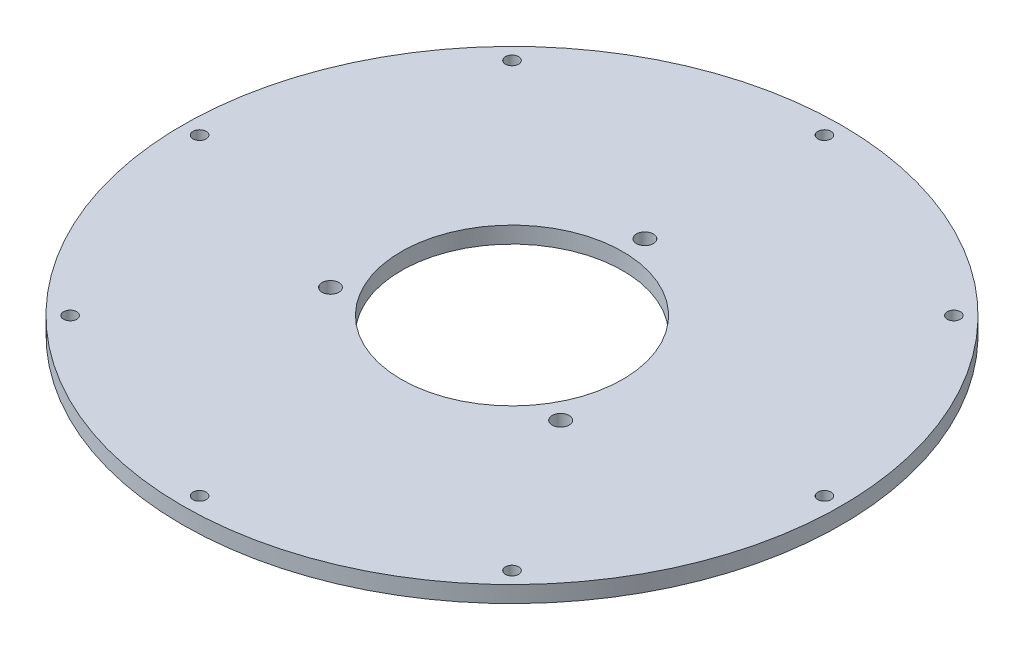
SolidWorks part; units mm, degrees
ref_plane "Front Plane" through (0, 0, 0) normal (0, 0, 1) x (1, 0, 0)
ref_plane "Top Plane" through (0, 0, 0) normal (0, 1, 0) x (1, 0, 0)
ref_plane "Right Plane" through (0, 0, 0) normal (1, 0, 0) x (0, 0, -1)
sketch "Sketch1" plane through (0, 0, 0) normal (0, 1, 0) x (1, 0, 0)
  circle A0 centre (0, 0) radius 62.5
  circle A1 centre (0, 0) radius 21
  circle A2 centre (0, 0) radius 21 construction
  dimension "D1" = 0
  dimension "D2" = 125
extrude "Boss-Extrude1" add sketch "Sketch1" along normal blind 3.125
sketch "Sketch2" plane through (0, 3.125, 0) normal (0, 1, 0) x (1, 0, 0)
  line L0 (0, 25.2) -> (0, 0) construction
  circle A0 centre (0, 25.2) radius 1.6
  circle A1 centre (21.8238, -12.6) radius 1.6
  circle A2 centre (-21.8238, -12.6) radius 1.6
  point P10 (0, 0)
  dimension "D2" = 3.2
  dimension "D3" = 3
extrude "Cut-Extrude1" cut sketch "Sketch2" against normal through all
sketch "Sketch5" plane through (0, 3.125, 0) normal (0, 1, 0) x (1, 0, 0)
  line L0 (3, 45.7275) -> (3, 31.607)
  line L1 (38.1011, 25.4618) -> (25.8724, 18.4016)
  line L2 (0, 0) -> (0, 62.5) construction
  line L3 (41.1011, -20.2657) -> (28.8724, -13.2054)
  line L4 (41.1011, 20.2657) -> (28.8724, 13.2054)
  line L5 (3, -45.7275) -> (3, -31.607)
  line L6 (38.1011, -25.4618) -> (25.8724, -18.4016)
  line L7 (-38.1011, -25.4618) -> (-25.8724, -18.4016)
  line L8 (-3, -45.7275) -> (-3, -31.607)
  line L9 (-41.1011, 20.2657) -> (-28.8724, 13.2054)
  line L10 (-41.1011, -20.2657) -> (-28.8724, -13.2054)
  line L11 (-3, 45.7275) -> (-3, 31.607)
  line L12 (-38.1011, 25.4618) -> (-25.8724, 18.4016)
  line L13 (3, 46.1306) -> (-3, 46.1306) construction
  circle A0 centre (0, 0) radius 62.5 construction
  arc A1 (4.6875, 29.6315) -> (23.3179, 18.8753) centre (0, 0) cw
  arc A2 (5.2174, 47.7156) -> (38.7142, 28.3762) centre (0, 0) cw
  arc A3 (38.7142, 28.3762) -> (38.1011, 25.4618) centre (37.1011, 27.1939) cw
  arc A4 (3, 45.7275) -> (5.2174, 47.7156) centre (5, 45.7275) cw
  arc A5 (23.3179, 18.8753) -> (25.8724, 18.4016) centre (24.8724, 20.1336) ccw
  arc A6 (3, 31.607) -> (4.6875, 29.6315) centre (5, 31.607) ccw
  arc A7 (28.0054, -10.7563) -> (28.8724, -13.2054) centre (29.8724, -11.4734) ccw
  arc A8 (43.9316, -19.3394) -> (41.1011, -20.2657) centre (42.1011, -18.5336) cw
  arc A9 (28.0054, 10.7563) -> (28.0054, -10.7563) centre (0, 0) cw
  arc A10 (28.8724, 13.2054) -> (28.0054, 10.7563) centre (29.8724, 11.4734) ccw
  arc A11 (41.1011, 20.2657) -> (43.9316, 19.3394) centre (42.1011, 18.5336) cw
  arc A12 (43.9316, 19.3394) -> (43.9316, -19.3394) centre (0, 0) cw
  arc A13 (4.6875, -29.6315) -> (3, -31.607) centre (5, -31.607) ccw
  arc A14 (5.2174, -47.7156) -> (3, -45.7275) centre (5, -45.7275) cw
  arc A15 (23.3179, -18.8753) -> (4.6875, -29.6315) centre (0, 0) cw
  arc A16 (25.8724, -18.4016) -> (23.3179, -18.8753) centre (24.8724, -20.1336) ccw
  arc A17 (38.1011, -25.4618) -> (38.7142, -28.3762) centre (37.1011, -27.1939) cw
  arc A18 (38.7142, -28.3762) -> (5.2174, -47.7156) centre (0, 0) cw
  arc A19 (-23.3179, -18.8753) -> (-25.8724, -18.4016) centre (-24.8724, -20.1336) ccw
  arc A20 (-38.7142, -28.3762) -> (-38.1011, -25.4618) centre (-37.1011, -27.1939) cw
  arc A21 (-4.6875, -29.6315) -> (-23.3179, -18.8753) centre (0, 0) cw
  arc A22 (-3, -31.607) -> (-4.6875, -29.6315) centre (-5, -31.607) ccw
  arc A23 (-3, -45.7275) -> (-5.2174, -47.7156) centre (-5, -45.7275) cw
  arc A24 (-5.2174, -47.7156) -> (-38.7142, -28.3762) centre (0, 0) cw
  arc A25 (-28.0054, 10.7563) -> (-28.8724, 13.2054) centre (-29.8724, 11.4734) ccw
  arc A26 (-43.9316, 19.3394) -> (-41.1011, 20.2657) centre (-42.1011, 18.5336) cw
  arc A27 (-28.0054, -10.7563) -> (-28.0054, 10.7563) centre (0, 0) cw
  arc A28 (-28.8724, -13.2054) -> (-28.0054, -10.7563) centre (-29.8724, -11.4734) ccw
  arc A29 (-41.1011, -20.2657) -> (-43.9316, -19.3394) centre (-42.1011, -18.5336) cw
  arc A30 (-43.9316, -19.3394) -> (-43.9316, 19.3394) centre (0, 0) cw
  arc A31 (-4.6875, 29.6315) -> (-3, 31.607) centre (-5, 31.607) ccw
  arc A32 (-5.2174, 47.7156) -> (-3, 45.7275) centre (-5, 45.7275) cw
  arc A33 (-23.3179, 18.8753) -> (-4.6875, 29.6315) centre (0, 0) cw
  arc A34 (-25.8724, 18.4016) -> (-23.3179, 18.8753) centre (-24.8724, 20.1336) ccw
  arc A35 (-38.1011, 25.4618) -> (-38.7142, 28.3762) centre (-37.1011, 27.1939) cw
  arc A36 (-38.7142, 28.3762) -> (-5.2174, 47.7156) centre (0, 0) cw
  point P80 (0, 0)
  point P82 (0, 46.1306)
  dimension "D1" = 2
  dimension "D4" = 30
  dimension "D5" = 48
  dimension "D3" = 6
  dimension "D2" = 6
extrude "Cut-Extrude2" [suppressed] cut sketch "Sketch5" against normal through all
sketch "Sketch6" plane through (0, 3.125, 0) normal (0, 1, 0) x (1, 0, 0)
  line L0 (59.25, 0) -> (-59.25, 0) construction
  line L1 (41.8961, -41.8961) -> (-41.8961, -41.8961) construction
  line L2 (41.8961, -41.8961) -> (41.8961, 41.8961) construction
  line L3 (41.8961, 41.8961) -> (-41.8961, 41.8961) construction
  line L4 (-41.8961, -41.8961) -> (-41.8961, 41.8961) construction
  line L5 (41.8961, -41.8961) -> (-41.8961, 41.8961) construction
  line L6 (41.8961, 41.8961) -> (-41.8961, -41.8961) construction
  line L7 (41.8961, 41.8961) -> (44.1942, 44.1942) construction
  line L8 (-59.25, 0) -> (-62.5, 0) construction
  line L9 (0, 0) -> (0, 59.25) construction
  line L10 (0, 0) -> (0, -59.25) construction
  circle A0 centre (-41.8961, 41.8961) radius 1.25
  circle A1 centre (41.8961, 41.8961) radius 1.25
  circle A2 centre (-41.8961, -41.8961) radius 1.25
  circle A3 centre (41.8961, -41.8961) radius 1.25
  circle A4 centre (-59.25, 0) radius 1.25
  circle A5 centre (59.25, 0) radius 1.25
  circle A6 centre (0, 0) radius 62.5 construction
  circle A7 centre (0, 0) radius 59.25 construction
  circle A8 centre (0, 59.25) radius 1.25
  circle A9 centre (0, -59.25) radius 1.25
  point P0 (0, 0)
  point P13 (0, 0)
  dimension "D2" = 2.5
  dimension "D4" = 2.5
  dimension "D1" = 3.25
  dimension "D3" = 3.25
extrude "Cut-Extrude3" cut sketch "Sketch6" against normal through all
sketch "Sketch7" [suppressed] plane through (0, 0, 0) normal (0, -1, 0) x (1, 0, 0)
  line L0 (28.2063, 55.7733) -> (25.7014, 54.8626) construction
  line L1 (25.2147, 53.6875) -> (25.7014, 54.8626) construction
  line L2 (20.1333, 55.7922) -> (20.6201, 56.9674) construction
  line L3 (20.6201, 56.9674) -> (19.4928, 59.3825) construction
  line L4 (28.2063, 55.7733) -> (25.7014, 54.8626)
  line L5 (25.2147, 53.6875) -> (25.7014, 54.8626)
  line L6 (20.1333, 55.7922) -> (20.6201, 56.9674)
  line L7 (20.6201, 56.9674) -> (19.4928, 59.3825)
  arc A0 (20.1333, 55.7922) -> (25.2147, 53.6875) centre (22.674, 54.7399) ccw construction
  arc A1 (20.1333, 55.7922) -> (25.2147, 53.6875) centre (22.674, 54.7399) ccw
  arc A2 (28.2063, 55.7733) -> (19.4928, 59.3825) centre (0, 0) ccw
extrude "Cut-Extrude4" [suppressed] cut sketch "Sketch7" against normal through all
equation "\"D3@Sketch6\"=\"D1@Sketch6\""
